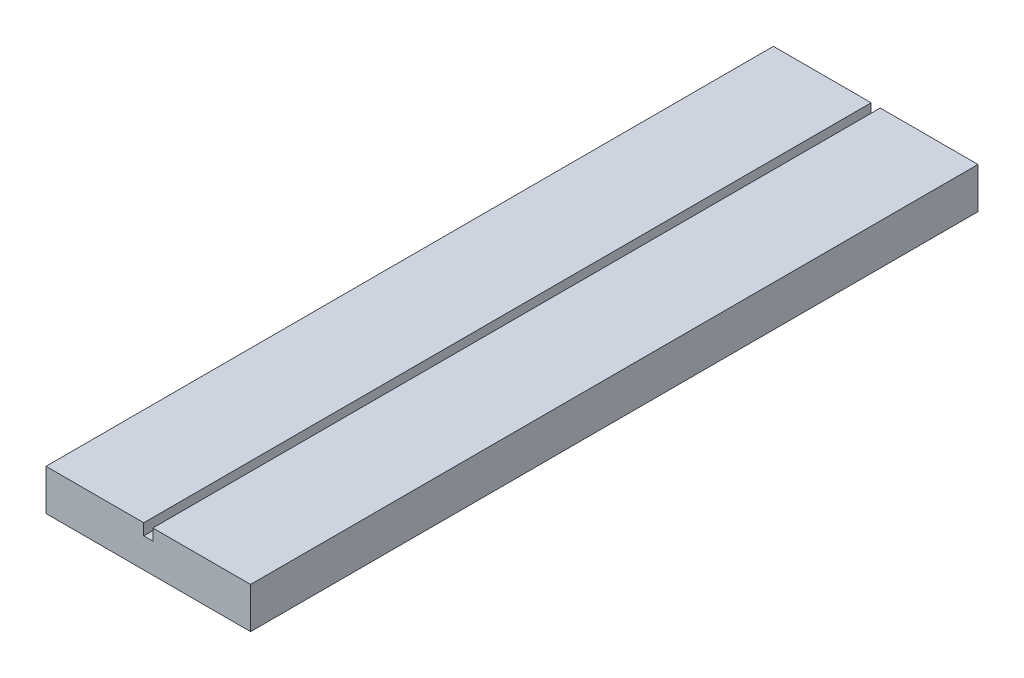
SolidWorks part; units mm, degrees
material "ABS"
ref_plane "Plan de face" through (0, 0, 0) normal (0, 0, 1) x (1, 0, 0)
ref_plane "Plan de dessus" through (0, 0, 0) normal (0, 1, 0) x (1, 0, 0)
ref_plane "Plan de droite" through (0, 0, 0) normal (1, 0, 0) x (0, 0, -1)
sketch "Esquisse1" plane through (0, 0, 0) normal (0, 1, 0) x (1, 0, 0)
  line L1 (-22.5, 80) -> (22.5, 80)
  line L2 (-22.5, 80) -> (-22.5, -80)
  line L3 (-22.5, -80) -> (22.5, -80)
  line L4 (22.5, 80) -> (22.5, -80)
  line L5 (-22.5, 80) -> (22.5, -80) construction
  line L6 (-22.5, -80) -> (22.5, 80) construction
  point P0 (0, 0)
  dimension "D1" = 160
  dimension "D2" = 45
extrude "Boss.-Extru.1" add sketch "Esquisse1" along normal blind 9
sketch "Esquisse3" plane through (0, 0, 80) normal (0, 0, 1) x (1, 0, 0)
  line L0 (0, 9) -> (0, 6.5) construction
  line L1 (-22.5, 9) -> (22.5, 9) construction
  line L2 (-1, 6.5) -> (1, 6.5)
  line L3 (-1, 6.5) -> (-1, 9)
  line L4 (1, 6.5) -> (1, 9)
  point P7 (0, 6.5)
  dimension "D1" = 2.5
  dimension "D2" = 2
extrude "Enlèv. mat.-Extru.1" cut sketch "Esquisse3" against normal through all and the other way through all
